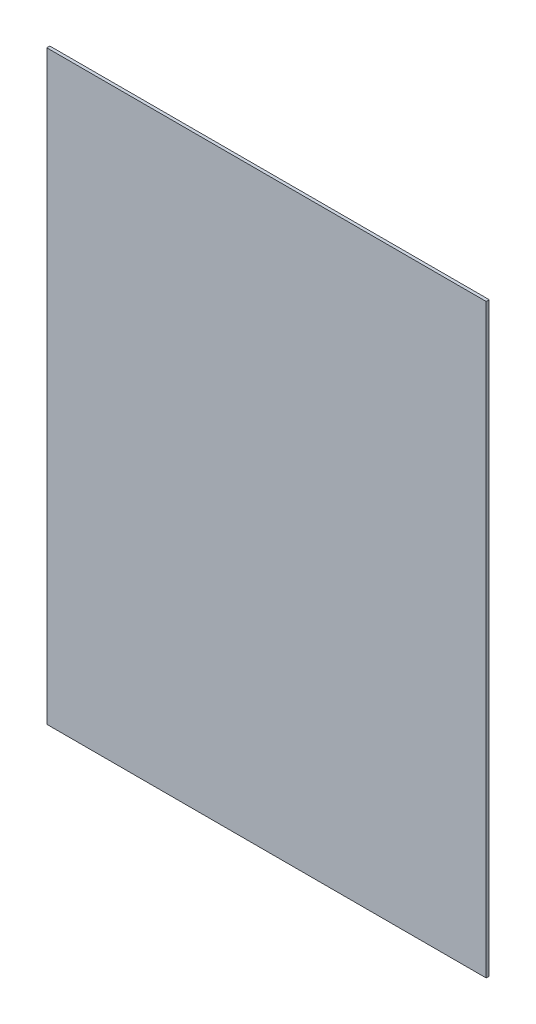
SolidWorks part; units mm, degrees
material "Pine"
ref_plane "X-Y Datum" through (0, 0, 0) normal (0, 0, 1) x (1, 0, 0)
ref_plane "X-Z Datum" through (0, 0, 0) normal (0, 1, 0) x (1, 0, 0)
ref_plane "Y-Z Datum" through (0, 0, 0) normal (1, 0, 0) x (0, 0, -1)
sketch "Sketch1" plane through (0, 0, 0) normal (0, 0, 1) x (1, 0, 0)
  line L1 (-457.2, 609.6) -> (457.2, 609.6)
  line L2 (-457.2, 609.6) -> (-457.2, -609.6)
  line L3 (-457.2, -609.6) -> (457.2, -609.6)
  line L4 (457.2, 609.6) -> (457.2, -609.6)
  line L5 (-457.2, 609.6) -> (457.2, -609.6) construction
  line L6 (-457.2, -609.6) -> (457.2, 609.6) construction
  point P0 (0, 0)
  dimension "D1" = 1219.2
  dimension "D2" = 914.4
extrude "Boss-Extrude1" add sketch "Sketch1" along normal blind 6.35
sketch "Sketch2" plane through (0, 0, 6.35) normal (0, 0, 1) x (1, 0, 0)
  line L0 (457.2, 609.6) -> (-457.2, 609.6) construction
  line L1 (102.87, -76.2) -> (204.47, -76.2)
  line L2 (102.87, -76.2) -> (102.87, -25.4)
  line L3 (102.87, -25.4) -> (204.47, -25.4)
  line L4 (204.47, -76.2) -> (204.47, -25.4)
  line L5 (457.2, -609.6) -> (457.2, 609.6) construction
  line L6 (127, 450.85) -> (127, 501.65)
  line L7 (127, 501.65) -> (76.2, 501.65)
  line L8 (101.0615, 263.89) -> (23.5973, 329.6309)
  line L9 (-69.85, -482.6) -> (-171.45, -482.6)
  line L10 (-69.85, -482.6) -> (-69.85, -431.8)
  line L11 (-69.85, -431.8) -> (-171.45, -431.8)
  line L12 (-171.45, -482.6) -> (-171.45, -431.8)
  line L13 (152.8424, 89.535) -> (178.2424, 89.535)
  line L14 (-457.2, -609.6) -> (457.2, -609.6) construction
  line L15 (152.8424, 89.535) -> (152.8424, 114.935)
  line L16 (152.8424, 114.935) -> (178.2424, 114.935)
  line L17 (178.2424, 89.535) -> (178.2424, 114.935)
  line L18 (152.8424, 89.535) -> (178.2424, 114.935) construction
  line L19 (152.8424, 114.935) -> (178.2424, 89.535) construction
  line L20 (-457.2, 609.6) -> (-457.2, -609.6) construction
  line L21 (-279.4, 127) -> (-177.8, 127)
  line L22 (-279.4, 127) -> (-279.4, 177.8)
  line L23 (-279.4, 177.8) -> (-177.8, 177.8)
  line L24 (-177.8, 127) -> (-177.8, 177.8)
  line L25 (-69.85, 127) -> (31.75, 127)
  line L26 (-69.85, 127) -> (-69.85, 177.8)
  line L27 (-69.85, 177.8) -> (31.75, 177.8)
  line L28 (31.75, 127) -> (31.75, 177.8)
  line L29 (62.6963, -354.7811) -> (149.821, -302.514)
  line L30 (-297.4206, 396.4799) -> (-246.6206, 396.4799)
  line L31 (-297.4206, 396.4799) -> (-297.4206, 498.0799)
  line L32 (-297.4206, 498.0799) -> (-246.6206, 498.0799)
  line L33 (-246.6206, 396.4799) -> (-246.6206, 498.0799)
  line L34 (-242.2858, -391.771) -> (-293.0858, -391.771)
  line L35 (-242.2858, -391.771) -> (-242.2858, -493.371)
  line L36 (-242.2858, -493.371) -> (-293.0858, -493.371)
  line L37 (-293.0858, -391.771) -> (-293.0858, -493.371)
  line L38 (62.6963, -354.7811) -> (36.5628, -311.2187)
  line L39 (36.5628, -311.2187) -> (123.6875, -258.9516)
  line L40 (149.821, -302.514) -> (123.6875, -258.9516)
  line L41 (229.0344, 164.6756) -> (127.4382, 163.8067)
  line L42 (229.0344, 164.6756) -> (228.6, 215.4738)
  line L43 (228.6, 215.4738) -> (127.0037, 214.6049)
  line L44 (127.4382, 163.8067) -> (127.0037, 214.6049)
  line L45 (101.0615, 263.89) -> (133.9319, 302.6221)
  line L46 (133.9319, 302.6221) -> (56.4678, 368.363)
  line L47 (23.5973, 329.6309) -> (56.4678, 368.363)
  line L48 (114.6205, -238.026) -> (150.0365, -274.4451)
  line L49 (114.6205, -238.026) -> (41.7824, -308.858)
  line L50 (150.0365, -274.4451) -> (77.1984, -345.2771)
  line L51 (41.7824, -308.858) -> (77.1984, -345.2771)
  line L53 (-246.6206, 498.0799) -> (-275.1956, 498.0799)
  line L54 (-246.6206, 498.0799) -> (-246.6206, 526.6549)
  line L55 (-246.6206, 526.6549) -> (-275.1956, 526.6549)
  line L56 (-275.1956, 498.0799) -> (-275.1956, 526.6549)
  line L57 (-246.6206, 396.4799) -> (-275.1956, 396.4799)
  line L58 (-246.6206, 396.4799) -> (-246.6206, 367.9049)
  line L59 (-246.6206, 367.9049) -> (-275.1956, 367.9049)
  line L60 (-275.1956, 396.4799) -> (-275.1956, 367.9049)
  line L61 (-242.2858, -493.371) -> (-270.8608, -493.371)
  line L62 (-270.8608, -363.196) -> (-242.2858, -363.196)
  line L63 (-270.8608, -363.196) -> (-270.8608, -391.771)
  line L64 (-270.8608, -391.771) -> (-242.2858, -391.771)
  line L65 (-242.2858, -363.196) -> (-242.2858, -391.771)
  line L66 (-242.2858, -493.371) -> (-242.2858, -521.946)
  line L67 (-242.2858, -521.946) -> (-270.8608, -521.946)
  line L68 (-270.8608, -493.371) -> (-270.8608, -521.946)
  line L69 (218.416, 270.51) -> (193.017, 270.2928)
  line L70 (218.416, 270.51) -> (218.6333, 245.1109)
  line L71 (218.6333, 245.1109) -> (193.2342, 244.8937)
  line L72 (193.017, 270.2928) -> (193.2342, 244.8937)
  line L73 (368.3, 85.725) -> (393.7, 85.725)
  line L74 (368.3, 85.725) -> (368.3, 111.125)
  line L75 (368.3, 111.125) -> (393.7, 111.125)
  line L76 (393.7, 85.725) -> (393.7, 111.125)
  point P17 (165.5424, 102.235)
  point P38 (-272.0206, 498.0799)
  point P75 (381, 111.125)
  dimension "D1" = 50.8
  dimension "D2" = 101.6
  dimension "D3" = 635
  dimension "D4" = 252.73
  dimension "D5" = 50.8
  dimension "D6" = 107.95
  dimension "D7" = 330.2
  dimension "D8" = 127
  dimension "D9" = 527.05
  dimension "D10" = 25.4
  dimension "D11" = 494.665
  dimension "D12" = 291.6576
  dimension "D13" = 177.8
  dimension "D14" = 431.8
  dimension "D15" = 209.55
  dimension "D16" = 111.5201
  dimension "D17" = 159.7794
  dimension "D18" = 164.1142
  dimension "D19" = 116.229
  dimension "D20" = 307.379
  dimension "D21" = 307.086
  dimension "D22" = 30.96
  dimension "D23" = 228.6
  dimension "D24" = 394.1262
  dimension "D25" = 89.51
  dimension "D26" = 306.9779
  dimension "D27" = 323.2681
  dimension "D28" = 49.68
  dimension "D29" = 44.2
  dimension "D30" = 307.1635
  dimension "D31" = 335.1549
  dimension "D32" = 28.575
  dimension "D33" = 238.784
  dimension "D34" = 339.09
  dimension "D35" = 498.475
  dimension "D36" = 63.5
